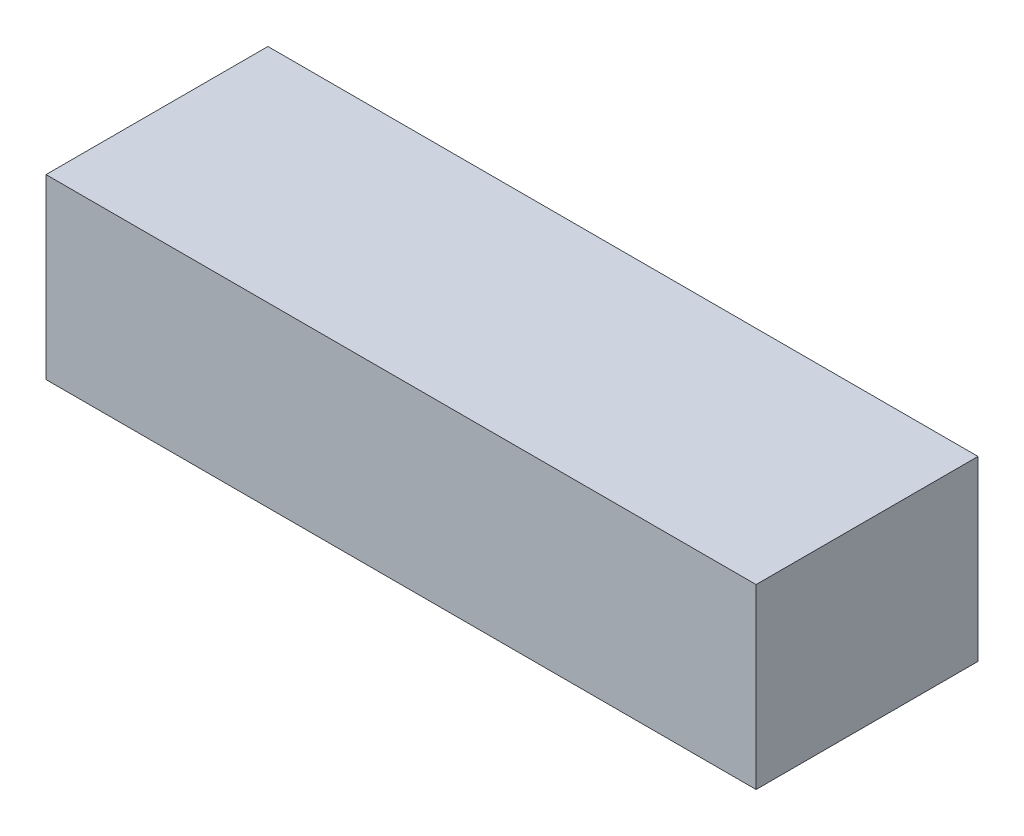
SolidWorks part; units mm, degrees
ref_plane "Front Plane" through (0, 0, 0) normal (0, 0, 1) x (1, 0, 0)
ref_plane "Top Plane" through (0, 0, 0) normal (0, 1, 0) x (1, 0, 0)
ref_plane "Right Plane" through (0, 0, 0) normal (1, 0, 0) x (0, 0, -1)
sketch "Sketch1" plane through (0, 0, 0) normal (0, 1, 0) x (1, 0, 0)
  line L0 (0, 0) -> (0, 12.7)
  line L1 (0, 12.7) -> (40.64, 12.7)
  line L2 (40.64, 12.7) -> (40.64, 0)
  line L3 (40.64, 0) -> (0, 0)
  dimension "D1" = 12.7
  dimension "D2" = 40.64
extrude "Boss-Extrude1" add sketch "Sketch1" along normal blind 10.16
